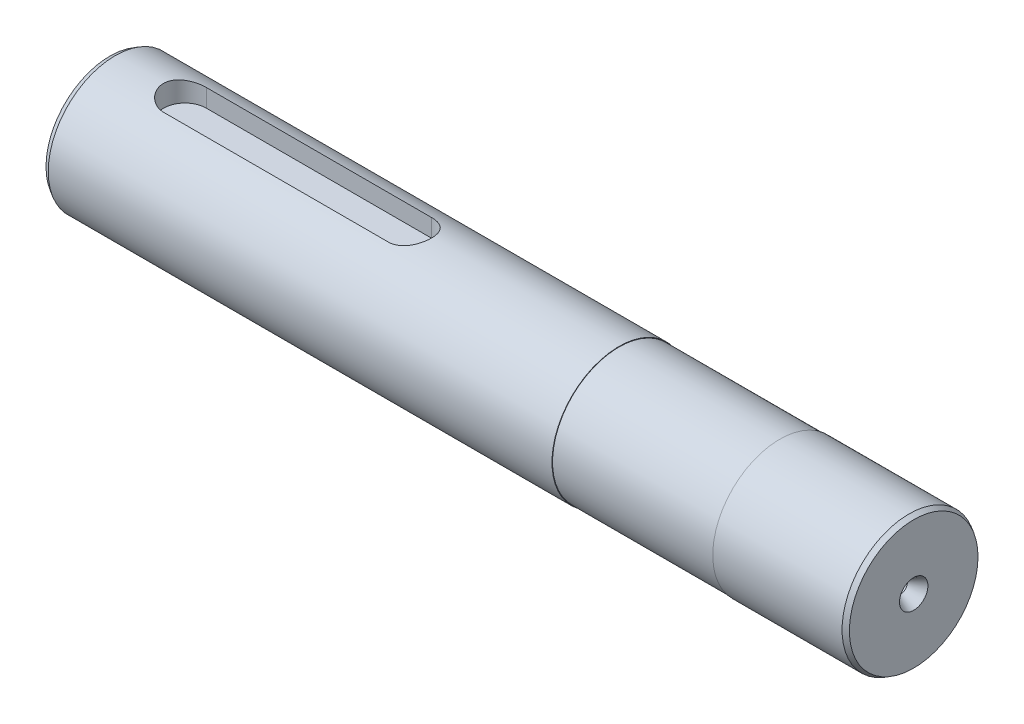
SolidWorks part; units mm, degrees
material "1.4305 (X8CrNiS18-9)"
ref_plane "Vorne" through (0, 0, 0) normal (0, 0, 1) x (1, 0, 0)
ref_plane "Oben" through (0, 0, 0) normal (0, 1, 0) x (1, 0, 0)
ref_plane "Rechts" through (0, 0, 0) normal (1, 0, 0) x (0, 0, -1)
sketch "Skizze1" plane through (0, 0, 0) normal (0, 1, 0) x (1, 0, 0)
  line L0 (0, 0) -> (-22.3789, 0) construction
  line L1 (0, 0) -> (0, 12.5)
  line L2 (0, 12.5) -> (95, 12.5)
  line L3 (125, 12.5) -> (125, 12.4)
  line L4 (125, 12.5) -> (149.134, 12.5)
  line L5 (150, 12) -> (150, 0)
  line L6 (150, 0) -> (0, 0)
  line L7 (95, 12.5) -> (95, 12.4)
  line L8 (95, 12.4) -> (125, 12.4)
  line L12 (149.134, 12.5) -> (150, 12)
  point P4 (0, 12.5)
  point P6 (125, 12.5)
  point P7 (150, 12.5)
  dimension "D1" = 25
  dimension "D2" = 25
  dimension "D3" = 150
  dimension "D4" = 25
  dimension "D5" = 0.1
  dimension "D6" = 30
  dimension "D11" = 0.5
  dimension "D12" = 30
revolve "Rotation1" add sketch "Skizze1" angle 360 about L0
sketch "Position" plane through (150, 0.5804, 2.1807) normal (1, 0, 0) x (0, 0, -1)
  line L0 (-2.3515, -0.5804) -> (2.1807, -0.5804) construction
  line L1 (2.1807, -0.5804) -> (2.1807, -5.1126) construction
  circle A0 centre (2.1807, -0.5804) radius 4.5323
  circle A1 centre (2.1807, -0.5804) radius 12 construction
ref_plane "Ebene1" through (150, 0, 0) normal (0, -1, 0) x (1, 0, 0)
sketch "Skizze3" plane through (150, 0, 0) normal (0, -1, 0) x (0, 0, -1)
  line L0 (0, 0) -> (0, -4.7988) construction
  line L2 (0, -5.3511) -> (1.25, -4.6)
  line L3 (1.25, -4.6) -> (1.25, -2.4249)
  line L4 (1.25, -2.4249) -> (2.65, 0)
  line L5 (2.65, 0) -> (0, 0)
  line L6 (0, 0) -> (0, -5.3511)
  dimension "w1" = 30
  dimension "w2" = 59
  dimension "d1" = 2.5
  dimension "d2" = 5.3
  dimension "t1" = 4.6
revolve "Schnitt-Rotation1" cut sketch "Skizze3" angle 360 about L0
other "DIN 332 - A<1>"
hole_wizard "M8 Gewindebohrung1" positions "Skizze32" profile "Skizze33" tap size "M8" standard "Gabler-Normteile"
sketch "Skizze32" plane through (0, 0, 0) normal (-1, 0, 0) x (0, 0, 1)
  point P0 (0, 0)
sketch "Skizze33" plane through (0, 0, 0) normal (0, 1, 0) x (0, 0, 1)
  line L0 (0, 0) -> (0, 24.2929)
  line L1 (0, 24.2929) -> (3.4, 22.25)
  line L2 (3.4, 22.25) -> (3.4, 1.9053)
  line L3 (3.4, 1.9053) -> (4.5, 0)
  line L5 (4.5, 0) -> (0, 0)
  line L6 (-3.4, 1.9053) -> (-4.5, 0) construction
  line L10 (0, 24.2929) -> (-3.4, 22.25) construction
  line L11 (0, -6.35) -> (0, 107.95) construction
  dimension "Bohrerdurchmesser" = 6.8
  dimension "Bohrungstiefe" = 22.25
  dimension "Senkdurchmesser (Oben)" = 9
  dimension "Senkwinkel (Oben)" = 60
  dimension "Spitzenwinkel" = 118
cosmetic thread "Bohrungsgewinde2" parameters "D1"=16, "D2"=8
chamfer "Fase1" distance 1 angle 30 1 edges at (0, 0, -12.5)
sketch "Positionierung" plane through (0, -8.5865, -9.842) normal (-1, 0, 0) x (0, 0, 1)
  line L1 (9.842, 8.5865) -> (22.342, 8.5865) construction
  line L2 (9.842, 8.5865) -> (9.842, 21.0865) construction
  circle A0 centre (9.842, 8.5865) radius 12.5
  circle A1 centre (9.842, 8.5865) radius 12.5 construction
  dimension "Positionswinkel" = 90
ref_plane "Profilebene" through (0, 12.5, 0) normal (0, 1, 0) x (-1, 0, 0)
sketch "Skizze2" plane through (0, 12.5, 4.921) normal (0, 1, 0) x (1, 0, 0)
  line L3 (14, 4.921) -> (56, 4.921) construction
  line L4 (14, 8.921) -> (56, 8.921)
  line L5 (14, 0.921) -> (56, 0.921)
  line L7 (1, 17.421) -> (1, -7.579) construction
  arc A2 (14, 8.921) -> (14, 0.921) centre (14, 4.921) ccw
  arc A3 (56, 0.921) -> (56, 8.921) centre (56, 4.921) ccw
  point P9 (35, 4.921)
  dimension "b" = 8
  dimension "Nutlaenge" = 50
  dimension "Abstand Stirnfläche" = 9
extrude "Schnitt-Linear austragen1" cut sketch "Skizze2" against normal blind 4
other "DIN 6885-1-aussen<1>"
